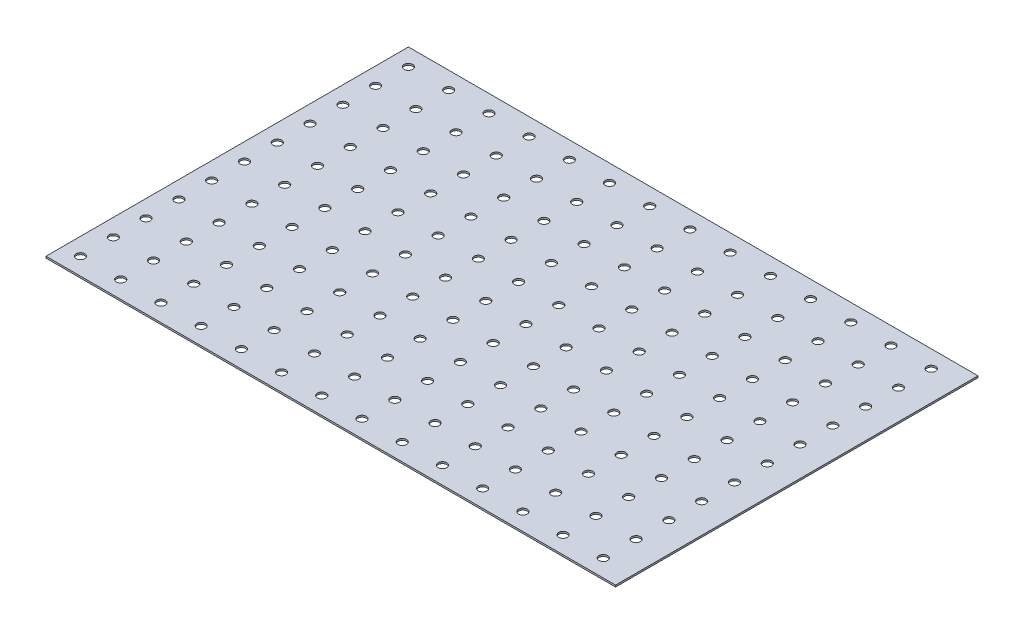
SolidWorks part; units mm, degrees
ref_plane "Front Plane" through (0, 0, 0) normal (0, 0, 1) x (1, 0, 0)
ref_plane "Top Plane" through (0, 0, 0) normal (0, 1, 0) x (1, 0, 0)
ref_plane "Right Plane" through (0, 0, 0) normal (1, 0, 0) x (0, 0, -1)
sketch "Sketch1" plane through (0, 0, 0) normal (0, 1, 0) x (1, 0, 0)
  line L1 (-208.3594, 98.8477) -> (121.6406, 98.8477)
  line L2 (-208.3594, 98.8477) -> (-208.3594, -111.1523)
  line L3 (-208.3594, -111.1523) -> (121.6406, -111.1523)
  line L4 (121.6406, 98.8477) -> (121.6406, -111.1523)
  circle A0 centre (-198.3594, 88.8477) radius 2.5
  circle A1 centre (-175.0594, 88.8477) radius 2.5
  circle A2 centre (-151.7594, 88.8477) radius 2.5
  circle A3 centre (-128.4594, 88.8477) radius 2.5
  circle A4 centre (-105.1594, 88.8477) radius 2.5
  circle A5 centre (-81.8594, 88.8477) radius 2.5
  circle A6 centre (-58.5594, 88.8477) radius 2.5
  circle A7 centre (-35.2594, 88.8477) radius 2.5
  circle A8 centre (-11.9594, 88.8477) radius 2.5
  circle A9 centre (11.3406, 88.8477) radius 2.5
  circle A10 centre (34.6406, 88.8477) radius 2.5
  circle A11 centre (57.9406, 88.8477) radius 2.5
  circle A12 centre (81.2406, 88.8477) radius 2.5
  circle A13 centre (104.5406, 88.8477) radius 2.5
  circle A15 centre (-175.0594, 69.8477) radius 2.5
  circle A16 centre (-151.7594, 69.8477) radius 2.5
  circle A17 centre (-128.4594, 69.8477) radius 2.5
  circle A18 centre (-105.1594, 69.8477) radius 2.5
  circle A19 centre (-81.8594, 69.8477) radius 2.5
  circle A20 centre (-58.5594, 69.8477) radius 2.5
  circle A21 centre (-35.2594, 69.8477) radius 2.5
  circle A22 centre (-11.9594, 69.8477) radius 2.5
  circle A23 centre (11.3406, 69.8477) radius 2.5
  circle A24 centre (34.6406, 69.8477) radius 2.5
  circle A25 centre (57.9406, 69.8477) radius 2.5
  circle A26 centre (81.2406, 69.8477) radius 2.5
  circle A27 centre (104.5406, 69.8477) radius 2.5
  circle A29 centre (-175.0594, 50.8477) radius 2.5
  circle A30 centre (-151.7594, 50.8477) radius 2.5
  circle A31 centre (-128.4594, 50.8477) radius 2.5
  circle A32 centre (-105.1594, 50.8477) radius 2.5
  circle A33 centre (-81.8594, 50.8477) radius 2.5
  circle A34 centre (-58.5594, 50.8477) radius 2.5
  circle A35 centre (-35.2594, 50.8477) radius 2.5
  circle A36 centre (-11.9594, 50.8477) radius 2.5
  circle A37 centre (11.3406, 50.8477) radius 2.5
  circle A38 centre (34.6406, 50.8477) radius 2.5
  circle A39 centre (57.9406, 50.8477) radius 2.5
  circle A40 centre (81.2406, 50.8477) radius 2.5
  circle A41 centre (104.5406, 50.8477) radius 2.5
  circle A43 centre (-175.0594, 31.8477) radius 2.5
  circle A44 centre (-151.7594, 31.8477) radius 2.5
  circle A45 centre (-128.4594, 31.8477) radius 2.5
  circle A46 centre (-105.1594, 31.8477) radius 2.5
  circle A47 centre (-81.8594, 31.8477) radius 2.5
  circle A48 centre (-58.5594, 31.8477) radius 2.5
  circle A49 centre (-35.2594, 31.8477) radius 2.5
  circle A50 centre (-11.9594, 31.8477) radius 2.5
  circle A51 centre (11.3406, 31.8477) radius 2.5
  circle A52 centre (34.6406, 31.8477) radius 2.5
  circle A53 centre (57.9406, 31.8477) radius 2.5
  circle A54 centre (81.2406, 31.8477) radius 2.5
  circle A55 centre (104.5406, 31.8477) radius 2.5
  circle A57 centre (-175.0594, 12.8477) radius 2.5
  circle A58 centre (-151.7594, 12.8477) radius 2.5
  circle A59 centre (-128.4594, 12.8477) radius 2.5
  circle A60 centre (-105.1594, 12.8477) radius 2.5
  circle A61 centre (-81.8594, 12.8477) radius 2.5
  circle A62 centre (-58.5594, 12.8477) radius 2.5
  circle A63 centre (-35.2594, 12.8477) radius 2.5
  circle A64 centre (-11.9594, 12.8477) radius 2.5
  circle A65 centre (11.3406, 12.8477) radius 2.5
  circle A66 centre (34.6406, 12.8477) radius 2.5
  circle A67 centre (57.9406, 12.8477) radius 2.5
  circle A68 centre (81.2406, 12.8477) radius 2.5
  circle A69 centre (104.5406, 12.8477) radius 2.5
  circle A71 centre (-175.0594, -6.1523) radius 2.5
  circle A72 centre (-151.7594, -6.1523) radius 2.5
  circle A73 centre (-128.4594, -6.1523) radius 2.5
  circle A74 centre (-105.1594, -6.1523) radius 2.5
  circle A75 centre (-81.8594, -6.1523) radius 2.5
  circle A76 centre (-58.5594, -6.1523) radius 2.5
  circle A77 centre (-35.2594, -6.1523) radius 2.5
  circle A78 centre (-11.9594, -6.1523) radius 2.5
  circle A79 centre (11.3406, -6.1523) radius 2.5
  circle A80 centre (34.6406, -6.1523) radius 2.5
  circle A81 centre (57.9406, -6.1523) radius 2.5
  circle A82 centre (81.2406, -6.1523) radius 2.5
  circle A83 centre (104.5406, -6.1523) radius 2.5
  circle A85 centre (-175.0594, -25.1523) radius 2.5
  circle A86 centre (-151.7594, -25.1523) radius 2.5
  circle A87 centre (-128.4594, -25.1523) radius 2.5
  circle A88 centre (-105.1594, -25.1523) radius 2.5
  circle A89 centre (-81.8594, -25.1523) radius 2.5
  circle A90 centre (-58.5594, -25.1523) radius 2.5
  circle A91 centre (-35.2594, -25.1523) radius 2.5
  circle A92 centre (-11.9594, -25.1523) radius 2.5
  circle A93 centre (11.3406, -25.1523) radius 2.5
  circle A94 centre (34.6406, -25.1523) radius 2.5
  circle A95 centre (57.9406, -25.1523) radius 2.5
  circle A96 centre (81.2406, -25.1523) radius 2.5
  circle A97 centre (104.5406, -25.1523) radius 2.5
  circle A99 centre (-175.0594, -44.1523) radius 2.5
  circle A100 centre (-151.7594, -44.1523) radius 2.5
  circle A101 centre (-128.4594, -44.1523) radius 2.5
  circle A102 centre (-105.1594, -44.1523) radius 2.5
  circle A103 centre (-81.8594, -44.1523) radius 2.5
  circle A104 centre (-58.5594, -44.1523) radius 2.5
  circle A105 centre (-35.2594, -44.1523) radius 2.5
  circle A106 centre (-11.9594, -44.1523) radius 2.5
  circle A107 centre (11.3406, -44.1523) radius 2.5
  circle A108 centre (34.6406, -44.1523) radius 2.5
  circle A109 centre (57.9406, -44.1523) radius 2.5
  circle A110 centre (81.2406, -44.1523) radius 2.5
  circle A111 centre (104.5406, -44.1523) radius 2.5
  circle A113 centre (-175.0594, -63.1523) radius 2.5
  circle A114 centre (-151.7594, -63.1523) radius 2.5
  circle A115 centre (-128.4594, -63.1523) radius 2.5
  circle A116 centre (-105.1594, -63.1523) radius 2.5
  circle A117 centre (-81.8594, -63.1523) radius 2.5
  circle A118 centre (-58.5594, -63.1523) radius 2.5
  circle A119 centre (-35.2594, -63.1523) radius 2.5
  circle A120 centre (-11.9594, -63.1523) radius 2.5
  circle A121 centre (11.3406, -63.1523) radius 2.5
  circle A122 centre (34.6406, -63.1523) radius 2.5
  circle A123 centre (57.9406, -63.1523) radius 2.5
  circle A124 centre (81.2406, -63.1523) radius 2.5
  circle A125 centre (104.5406, -63.1523) radius 2.5
  circle A127 centre (-175.0594, -82.1523) radius 2.5
  circle A128 centre (-151.7594, -82.1523) radius 2.5
  circle A129 centre (-128.4594, -82.1523) radius 2.5
  circle A130 centre (-105.1594, -82.1523) radius 2.5
  circle A131 centre (-81.8594, -82.1523) radius 2.5
  circle A132 centre (-58.5594, -82.1523) radius 2.5
  circle A133 centre (-35.2594, -82.1523) radius 2.5
  circle A134 centre (-11.9594, -82.1523) radius 2.5
  circle A135 centre (11.3406, -82.1523) radius 2.5
  circle A136 centre (34.6406, -82.1523) radius 2.5
  circle A137 centre (57.9406, -82.1523) radius 2.5
  circle A138 centre (81.2406, -82.1523) radius 2.5
  circle A139 centre (104.5406, -82.1523) radius 2.5
  circle A141 centre (-175.0594, -101.1523) radius 2.5
  circle A142 centre (-151.7594, -101.1523) radius 2.5
  circle A143 centre (-128.4594, -101.1523) radius 2.5
  circle A144 centre (-105.1594, -101.1523) radius 2.5
  circle A145 centre (-81.8594, -101.1523) radius 2.5
  circle A146 centre (-58.5594, -101.1523) radius 2.5
  circle A147 centre (-35.2594, -101.1523) radius 2.5
  circle A148 centre (-11.9594, -101.1523) radius 2.5
  circle A149 centre (11.3406, -101.1523) radius 2.5
  circle A150 centre (34.6406, -101.1523) radius 2.5
  circle A151 centre (57.9406, -101.1523) radius 2.5
  circle A152 centre (81.2406, -101.1523) radius 2.5
  circle A153 centre (104.5406, -101.1523) radius 2.5
  circle A155 centre (-198.3594, 69.8477) radius 2.5
  circle A156 centre (-198.3594, 50.8477) radius 2.5
  circle A157 centre (-198.3594, 31.8477) radius 2.5
  circle A158 centre (-198.3594, 12.8477) radius 2.5
  circle A159 centre (-198.3594, -6.1523) radius 2.5
  circle A160 centre (-198.3594, -25.1523) radius 2.5
  circle A161 centre (-198.3594, -44.1523) radius 2.5
  circle A162 centre (-198.3594, -63.1523) radius 2.5
  circle A163 centre (-198.3594, -82.1523) radius 2.5
  circle A164 centre (-198.3594, -101.1523) radius 2.5
  circle A165 centre (127.8406, 88.8477) radius 2.5 [skipped]
  circle A166 centre (127.8406, 69.8477) radius 2.5 [skipped]
  circle A167 centre (127.8406, -101.1523) radius 2.5 [skipped]
  circle A168 centre (127.8406, -63.1523) radius 2.5 [skipped]
  circle A169 centre (127.8406, -82.1523) radius 2.5 [skipped]
  circle A170 centre (127.8406, -44.1523) radius 2.5 [skipped]
  circle A171 centre (127.8406, -25.1523) radius 2.5 [skipped]
  circle A172 centre (127.8406, 12.8477) radius 2.5 [skipped]
  circle A173 centre (127.8406, 31.8477) radius 2.5 [skipped]
  circle A174 centre (127.8406, 50.8477) radius 2.5 [skipped]
  circle A175 centre (127.8406, -6.1523) radius 2.5 [skipped]
  point P6 (0, 0)
  point P7 (0, 0)
  dimension "D3" = 5
  dimension "D1" = 210
  dimension "D2" = 330
  dimension "D4" = 10
  dimension "D5" = 10
  dimension "D6" = 15
  dimension "D7" = 11
extrude "Boss-Extrude1" add sketch "Sketch1" along normal blind 1
